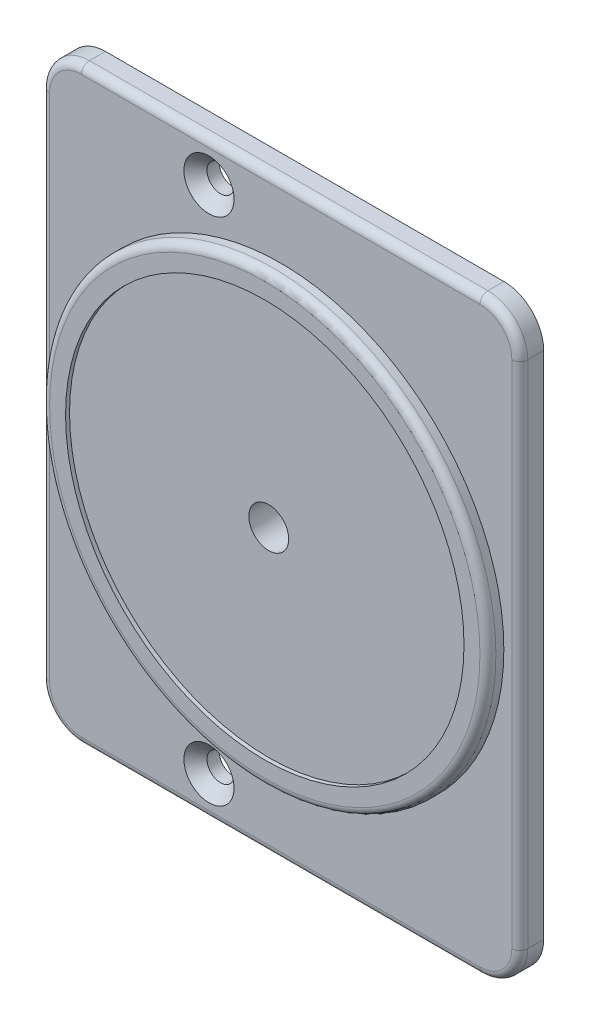
SolidWorks part; units mm, degrees
ref_plane "Face" through (0, 0, 0) normal (0, 0, 1) x (1, 0, 0)
ref_plane "Dessus" through (0, 0, 0) normal (0, 1, 0) x (1, 0, 0)
ref_plane "Droite" through (0, 0, 0) normal (1, 0, 0) x (0, 0, -1)
sketch "Esquisse1" plane through (0, 0, 0) normal (0, 0, 1) x (1, 0, 0)
  line L1 (-30, 37) -> (30, 37)
  line L2 (-30, 37) -> (-30, -37)
  line L3 (-30, -37) -> (30, -37)
  line L4 (30, 37) -> (30, -37)
  dimension "D1" = 37
  dimension "D2" = 74
  dimension "D3" = 30
  dimension "D4" = 60
extrude "Boss.-Extru.1" add sketch "Esquisse1" against normal blind 3
sketch "Esquisse2" plane through (0, 0, 0) normal (0, 0, 1) x (1, 0, 0)
  circle A0 centre (0, 0) radius 28
  dimension "D1" = 56
extrude "Boss.-Extru.2" add sketch "Esquisse2" along normal blind 2
sketch "Esquisse6" plane through (0, 0, 2) normal (0, 0, 1) x (1, 0, 0)
  circle A0 centre (0, 0) radius 25
  dimension "D1" = 50
extrude "Enlèv. mat.-Extru.4" cut sketch "Esquisse6" against normal blind 0.5
fillet "Congé 5" radius 5 4 edges at (30, -37, -1.5) (-30, -37, -1.5) (30, 37, -1.5) (-30, 37, -1.5)
fillet "Congé1" radius 1 9 edges at (28.5355, 35.5355, 0) (30, 0, 0) (28.5355, -35.5355, 0) (0, -37, 0) (-28.5355, -35.5355, 0) (-30, 0, 0) (-28.5355, 35.5355, 0) (0, 37, 0) (28, 0, 2)
chamfer "Chanfrein1" [suppressed] distance 0.2 angle 45
sketch "Esquisse7" plane through (0, 0, -3) normal (0, 0, -1) x (-1, 0, 0)
  circle A0 centre (0, 0) radius 2.5
  dimension "D1" = 5
extrude "Enlèv. mat.-Extru.5" cut sketch "Esquisse7" against normal through all
hole_wizard "Fraisage pour vis à tête fraisée M31" positions "Esquisse9" profile "Esquisse8" countersink size "M3" standard "Din" end condition up to next
sketch "Esquisse9" plane through (0, 0, 0) normal (0, 0, 1) x (1, 0, 0)
  circle A0 centre (0, 0) radius 2.5 construction
  point P5 (-9, 32)
  point P13 (-9, -32)
  dimension "D1" = 9
  dimension "D2" = 9
  dimension "D3" = 32
  dimension "D4" = 32
sketch "Esquisse8" plane through (-9, 32, 0) normal (1, 0, 0) x (0, -1, 0)
  line L0 (0, 0) -> (0, 3)
  line L1 (0, 3) -> (1.7, 3)
  line L2 (1.7, 3) -> (1.7, 1.45)
  line L3 (1.7, 1.45) -> (3.15, 0)
  line L5 (3.15, 0) -> (0, 0)
  line L6 (-1.7, 1.45) -> (-3.15, 0) construction
  line L11 (0, -6.35) -> (0, 107.95) construction
  dimension "Diamètre du perçage jusqu'au prochain" = 3.4
  dimension "Profondeur du perçage jusqu'au prochain" = 3
  dimension "Diamètre du fraisage entrant" = 6.3
  dimension "Angle du fraisage entrant" = 90
